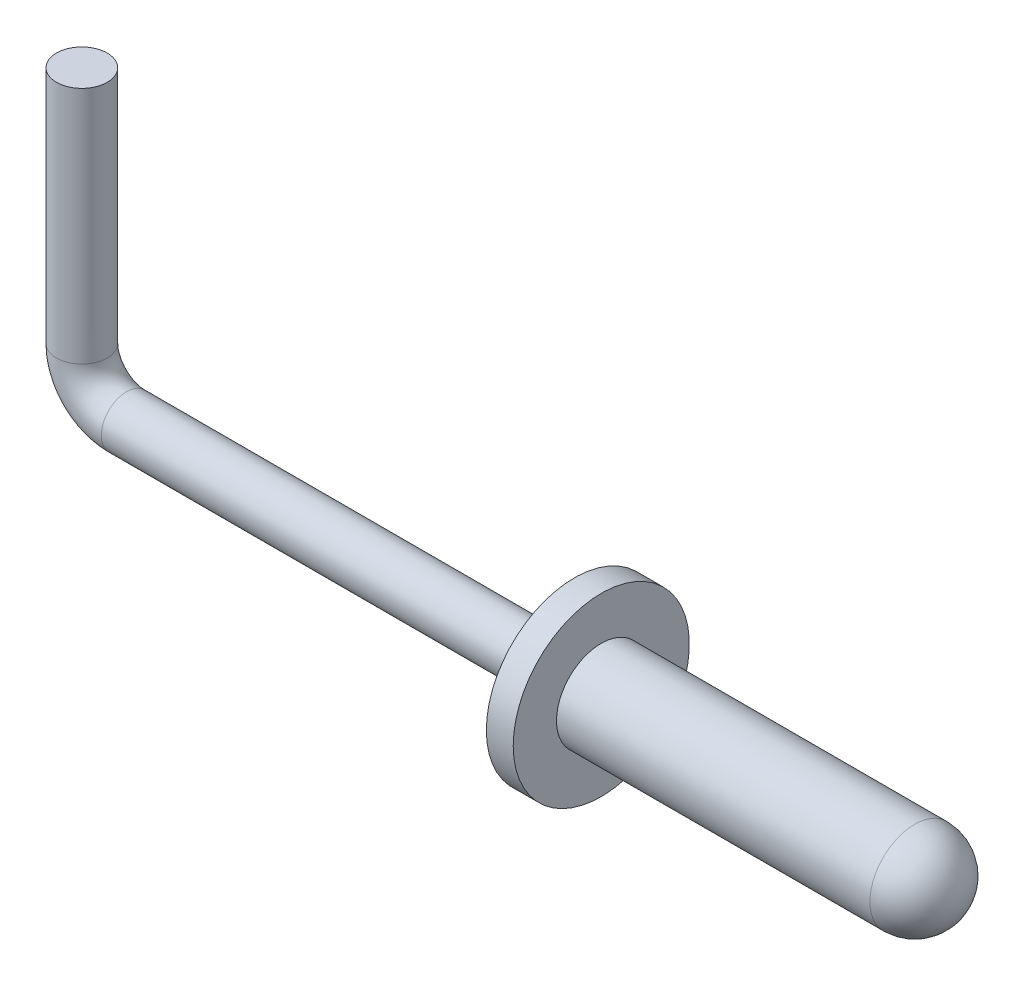
SolidWorks part; units mm, degrees
ref_plane "Front Plane" through (0, 0, 0) normal (0, 0, 1) x (1, 0, 0)
ref_plane "Top Plane" through (0, 0, 0) normal (0, 1, 0) x (1, 0, 0)
ref_plane "Right Plane" through (0, 0, 0) normal (1, 0, 0) x (0, 0, -1)
sketch "Sketch1" plane through (0, 0, 0) normal (1, 0, 0) x (0, 0, -1)
  circle A0 centre (0, 0) radius 1.5
  dimension "D1" = 3
extrude "Boss-Extrude1" add sketch "Sketch1" along normal blind 10.5
sketch "Sketch8" plane through (10.5, 0, 0) normal (1, 0, 0) x (0, 0, -1)
  line L0 (1.5, 0) -> (-1.5, 0)
  circle A1 centre (0, 0) radius 1.5
  arc A2 (1.5, 0) -> (-1.5, 0) centre (0, 0) ccw
  dimension "D1" = 0
revolve "Revolve1" add sketch "Sketch8" angle 360 about L0
sketch "Sketch2" plane through (0, 0, 0) normal (-1, 0, 0) x (0, 0, 1)
  circle A0 centre (0, 0) radius 2.95
  dimension "D1" = 5.9
extrude "Boss-Extrude2" add sketch "Sketch2" along normal blind 0.9 contours A0
sketch "Sketch3" plane through (0, 0, 0) normal (0, 0, 1) x (1, 0, 0)
  line L0 (-0.9, 0) -> (-15.9, 0)
  line L1 (-0.9, 2.95) -> (-0.9, -2.95) construction
  line L2 (-17.4, 1.5) -> (-17.4, 9.5)
  arc A0 (-15.9, 0) -> (-17.4, 1.5) centre (-15.9, 1.5) cw
  dimension "D1" = 1.5
  dimension "D2" = 8
  dimension "D3" = 15
sweep "Sweep1" add path "Sketch3" circular profile diameter 1.7 parameters "D3"=1.7
